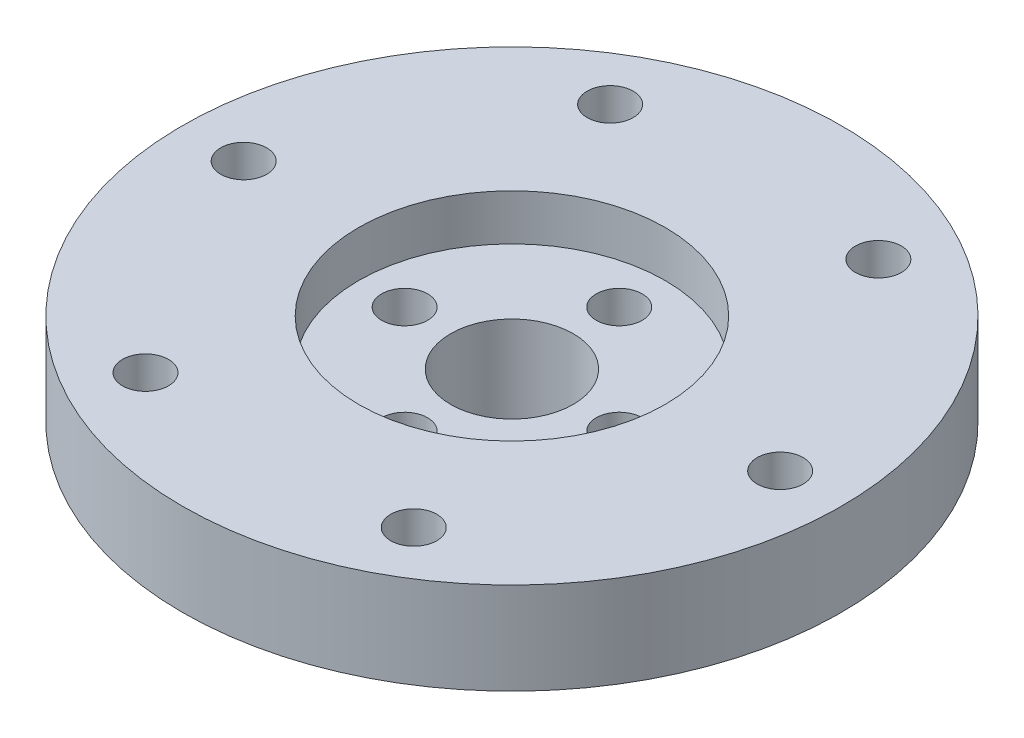
SolidWorks part; units mm, degrees
material "聚脂树脂"
ref_plane "前视基准面" through (0, 0, 0) normal (0, 0, 1) x (1, 0, 0)
ref_plane "上视基准面" through (0, 0, 0) normal (0, 1, 0) x (1, 0, 0)
ref_plane "右视基准面" through (0, 0, 0) normal (1, 0, 0) x (0, 0, -1)
other "Configuration Table"
sketch "草图1" plane through (0, 0, 0) normal (0, 1, 0) x (1, 0, 0)
  line L0 (0, 0) -> (14.4498, 0) construction
  line L1 (0, 0) -> (0, 16.8215) construction
  line L2 (0, 0) -> (9.0448, 15.666) construction
  circle A0 centre (0, 0) radius 7 construction
  circle A1 centre (0, 0) radius 4
  circle A2 centre (0, 0) radius 21.5
  circle A3 centre (0, 7) radius 1.5
  circle A4 centre (7, 0) radius 1.5
  circle A5 centre (0, -7) radius 1.5
  circle A6 centre (-7, 0) radius 1.5
  circle A9 centre (8.75, 15.1554) radius 1.5
  circle A10 centre (17.5, 0) radius 1.5
  circle A11 centre (-17.5, 0) radius 1.5
  circle A12 centre (-8.75, 15.1554) radius 1.5
  circle A13 centre (8.75, -15.1554) radius 1.5
  circle A14 centre (-8.75, -15.1554) radius 1.5
  dimension "D1" = 3
  dimension "D2" = 3
  dimension "D3" = 14
  dimension "D4" = 8
  dimension "D5" = 43
  dimension "D7" = 3
  dimension "D8" = 3
  dimension "D6" = 60
  dimension "D9" = 17.5
  dimension "D10" = 17.5
extrude "凸台-拉伸1" add sketch "草图1" along normal blind 3
sketch "草图2" plane through (0, 3, 0) normal (0, 1, 0) x (1, 0, 0)
  circle A0 centre (-17.5, 0) radius 1.5 construction
  circle A1 centre (-8.75, -15.1554) radius 1.5 construction
  circle A2 centre (8.75, -15.1554) radius 1.5 construction
  circle A3 centre (17.5, 0) radius 1.5 construction
  circle A4 centre (8.75, 15.1554) radius 1.5 construction
  circle A5 centre (-8.75, 15.1554) radius 1.5 construction
  circle A6 centre (-17.5, 0) radius 1.5
  circle A7 centre (-8.75, -15.1554) radius 1.5
  circle A8 centre (8.75, -15.1554) radius 1.5
  circle A9 centre (17.5, 0) radius 1.5
  circle A10 centre (8.75, 15.1554) radius 1.5
  circle A11 centre (-8.75, 15.1554) radius 1.5
  circle A12 centre (0, 0) radius 10
  circle A13 centre (0, 0) radius 21.5
  dimension "D1" = 20
  dimension "D2" = 43
extrude "凸台-拉伸2" add sketch "草图2" along normal blind 3
sketch "草图3" plane through (0, 0, 0) normal (0, -1, 0) x (1, 0, 0)
  circle A0 centre (0, 0) radius 14
  circle A1 centre (7, 0) radius 1.5 construction
  circle A2 centre (0, 0) radius 4 construction
  circle A3 centre (0, -7) radius 1.5 construction
  circle A4 centre (-7, 0) radius 1.5 construction
  circle A5 centre (0, 7) radius 1.5 construction
  circle A6 centre (7, 0) radius 1.5
  circle A7 centre (0, 0) radius 4
  circle A8 centre (0, -7) radius 1.5
  circle A9 centre (-7, 0) radius 1.5
  circle A10 centre (0, 7) radius 1.5
  dimension "D1" = 28
extrude "凸台-拉伸3" add sketch "草图3" along normal blind 3
